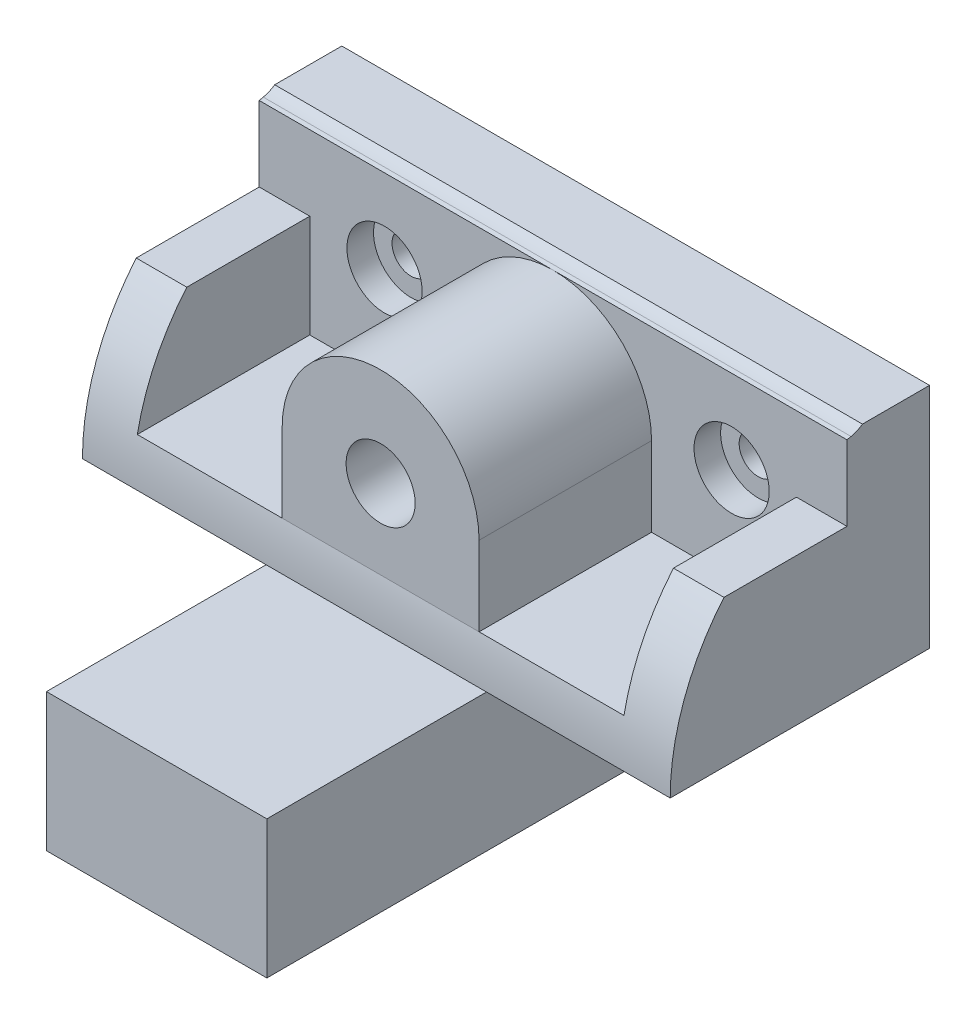
SolidWorks part; units mm, degrees
material "Gray Cast Iron"
ref_plane "Front Plane" through (0, 0, 0) normal (0, 0, 1) x (1, 0, 0)
ref_plane "Top Plane" through (0, 0, 0) normal (0, 1, 0) x (1, 0, 0)
ref_plane "Right Plane" through (0, 0, 0) normal (1, 0, 0) x (0, 0, -1)
sketch "Sketch1" plane through (0, 0, 0) normal (1, 0, 0) x (0, 0, -1)
  line L0 (35.433, 45.212) -> (35.433, 43.6477)
  line L1 (0, 0) -> (44.831, 0)
  line L3 (35.433, 45.212) -> (44.831, 45.212)
  line L4 (44.831, 0) -> (44.831, 45.212)
  arc A0 (0, 0) -> (31.2593, 38.5064) centre (39.3465, 0) cw
  arc A1 (31.2593, 38.5064) -> (35.433, 43.6477) centre (30.1796, 43.6477) ccw
  dimension "D1" = 9.398
  dimension "D3" = 44.831
  dimension "D2" = 45.212
  dimension "D4" = 38.5064
extrude "Jaw side extrude" add sketch "Sketch1" along normal blind 101.6
sketch "Sketch2" plane through (0, 45.212, 0) normal (0, 1, 0) x (1, 0, 0)
  line L1 (8.7376, 0) -> (92.8624, 0)
  line L2 (8.7376, 0) -> (8.7376, 30.5562)
  line L3 (8.7376, 30.5562) -> (92.8624, 30.5562)
  line L4 (101.6, 0) -> (101.6, 44.831)
  line L5 (101.6, 0) -> (101.6, 44.831) construction
  line L6 (0, 0) -> (101.6, 0)
  line L7 (0, 0) -> (101.6, 0) construction
  line L8 (0, 44.831) -> (0, 0)
  line L9 (0, 44.831) -> (0, 0) construction
  line L10 (101.6, 44.831) -> (0, 44.831)
  line L11 (101.6, 44.831) -> (0, 44.831) construction
  line L12 (92.8624, 0) -> (92.8624, 30.5562)
  point P0 (50.8, 0)
  dimension "D2" = 8.7376
  dimension "D3" = 14.2748
  dimension "D1" = 0
extrude "Hollow cut extrude" cut sketch "Sketch2" against normal blind 37.592
sketch "Sketch3" plane through (0, 0, -30.5562) normal (0, 0, 1) x (1, 0, 0)
  line L0 (50.8, 38.352) -> (50.8, 7.62) construction
  line L2 (92.8624, 7.62) -> (8.7376, 7.62) construction
  line L3 (67.818, 7.62) -> (67.818, 21.334)
  line L4 (33.782, 21.334) -> (33.782, 7.62)
  line L5 (33.782, 7.62) -> (67.818, 7.62)
  line L6 (8.7376, 38.352) -> (92.8624, 38.352) construction
  arc A0 (67.818, 21.334) -> (33.782, 21.334) centre (50.8, 21.334) ccw
  circle A1 centre (50.8, 21.334) radius 5.969
  dimension "D2" = 11.938
  dimension "D1" = 34.036
extrude "Screw boss extrude" add sketch "Sketch3" along normal up to vertex (29.8113 mm away)
sketch "Sketch5" plane through (0, 0, -44.831) normal (0, 0, -1) x (-1, 0, 0)
  line L0 (-50.8, 45.212) -> (-50.8, 0) construction
  line L1 (-101.6, 45.212) -> (0, 45.212) construction
  line L2 (-101.6, 0) -> (0, 0) construction
  line L3 (-69.85, -23.8252) -> (-69.85, 0)
  line L4 (-69.85, -23.8252) -> (-31.75, -23.8252)
  line L5 (-69.85, 0) -> (-31.75, 0)
  line L6 (-31.75, -23.8252) -> (-31.75, 0)
  line L7 (-69.85, -23.8252) -> (-31.75, 0) construction
  line L8 (-69.85, 0) -> (-31.75, -23.8252) construction
  point P6 (-50.8, 0)
  point P7 (-50.8, -11.9126)
  point P8 (-50.8, 45.212)
  dimension "D1" = 38.1
  dimension "D2" = 23.8252
extrude "Foot extrude" add sketch "Sketch5" against normal blind 82.804 contours L4 L6 L5 L3
hole_wizard "CBORE for M6 Pan Head Machine Screw1" positions "Sketch6" profile "Sketch7" counterbore size "M6" standard "ANSI Metric" end condition through all
sketch "Sketch6" plane through (50.8, -38.1, -30.5562) normal (0, 0, 1) x (1, 0, 0)
  line L0 (-29.143, 61.9649) -> (30.8599, 61.9649) construction
  line L1 (0, 76.452) -> (0, 39.5098) construction
  point P0 (-29.143, 61.9649)
  point P1 (30.8599, 61.9649)
sketch "Sketch7" plane through (21.657, 23.8649, -30.5562) normal (1, 0, 0) x (0, -1, 0)
  line L0 (0, 0) -> (0, 14.2748)
  line L1 (0, 14.2748) -> (3.3, 14.2748)
  line L3 (3.3, 14.2748) -> (3.3, 4.6)
  line L4 (3.3, 4.6) -> (6.5, 4.6)
  line L5 (6.5, 4.6) -> (6.5, 0)
  line L7 (6.5, 0) -> (0, 0)
  line L11 (0, -6.35) -> (0, 107.95) construction
  dimension "Thru Hole Dia." = 6.6
  dimension "Thru Hole Depth" = 14.2748
  dimension "C'Bore Dia." = 13
  dimension "C'Bore Depth" = 4.6
sketch "Sketch12" plane through (0, 0, 0) normal (-1, 0, 0) x (0, 0, 1)
  line L0 (0, 0) -> (-44.831, 0) construction
  line L1 (-44.831, 45.212) -> (-30.1796, 45.212)
  line L2 (-44.831, 45.212) -> (-44.831, 39.37)
  line L3 (-44.831, 39.37) -> (-30.1796, 39.37)
  line L4 (-30.1796, 45.212) -> (-30.1796, 39.37)
  dimension "D1" = 39.37
extrude "top trim Cut-Extrude3" cut sketch "Sketch12" against normal through all
sketch "Sketch13" plane through (8.7376, 0, 0) normal (-1, 0, 0) x (0, 0, 1)
  line L0 (0, 0) -> (-44.831, 0) construction
  line L1 (-30.5562, 38.352) -> (-7.1133, 38.352)
  line L2 (-30.5562, 38.352) -> (-30.5562, 25.4)
  line L3 (-30.5562, 25.4) -> (-7.1133, 25.4)
  line L4 (-7.1133, 38.352) -> (-7.1133, 25.4)
  dimension "D1" = 25.4
extrude "web trim 1 Cut-Extrude4" cut sketch "Sketch13" along normal up to surface (8.7376 mm away) up to face at (0, 24.538, -29.4728)
sketch "Sketch14" plane through (92.8624, 0, 0) normal (1, 0, 0) x (0, 0, -1)
  line L0 (0, 0) -> (44.831, 0) construction
  line L1 (30.5562, 38.352) -> (-7.3223, 38.352)
  line L2 (30.5562, 38.352) -> (30.5562, 25.4)
  line L3 (30.5562, 25.4) -> (-7.3223, 25.4)
  line L4 (-7.3223, 38.352) -> (-7.3223, 25.4)
  line L5 (30.5562, 7.62) -> (30.5562, 38.352) construction
  arc A0 (30.5562, 38.352) -> (0.7449, 7.62) centre (39.3465, 0) ccw construction
  dimension "D1" = 25.4
extrude "web trim 2 Cut-Extrude5" cut sketch "Sketch14" against normal up to surface (8.7376 mm away)
equation "\"delta-z\"= 1.5"
equation "\"max-tube-diam\"= 3.5"
equation "\"v-block-notch-height\"= 1.5"
equation "\"v-block-notch-angle\"= 120"
equation "\"jaw-travel\"= 4.45"
equation "\"jaw-width\"= 4"
equation "\"rib-top-width\"= 0.5"
equation "\"rib-side-width\"= 0.5"
equation "\"quarter-twenty-close-clearance\"= .257"
equation "\"box-way-width\"= 1.5"
equation "\"box-way-depth\"= 1.5"
equation "\"D1@Sketch5\"=\"box-way-width\""
equation "\"D2@Sketch1\"=\"jaw-height\""
equation "\"total-height\"= 3.28"
equation "\"mid-height\"= 1.5"
equation "\"screw-OD\"= .625"
equation "\"screw-reduced-diam\"= .47"
equation "\"jaw-height\"= \"total-height\" - \"mid-height\""
equation "\"D2@Sketch3\"=\"screw-reduced-diam\""
equation "\"jaw-mod-plate-thickness\"= .375"
equation "\"jaw-mod-plate-extension-thickness\"= .15"
equation "\"jaw-mod-height\"=  \"max-tube-diam\"/2 + \"delta-z\" + \"v-block-notch-height\"/2"
equation "\"pressure-plate-OD\"= 6.75"
equation "\"swivel-cleat-thick\"= .5"
equation "\"swivel-gap\"= .02"
equation "\"D1@web trim 1 Cut-Extrude4\"=\"jaw-mod-plate-thickness\""
equation "\"D1@web trim 2 Cut-Extrude5\"=\"jaw-mod-plate-thickness\""
